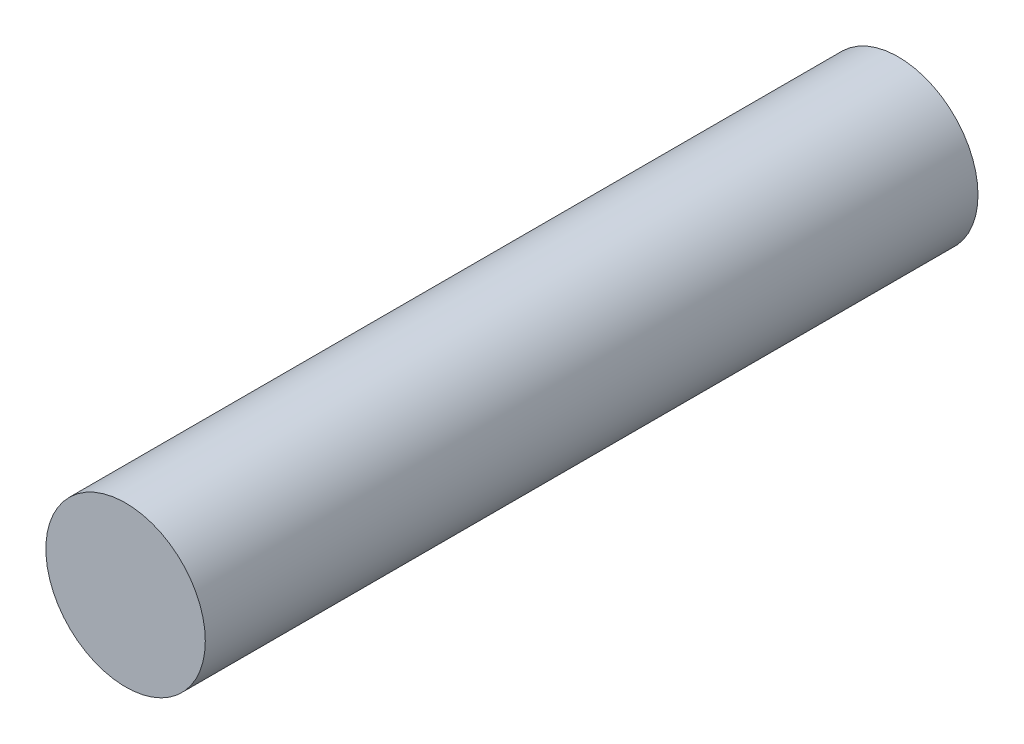
SolidWorks part; units mm, degrees
ref_plane "Front Plane" through (0, 0, 0) normal (0, 0, 1) x (1, 0, 0)
ref_plane "Top Plane" through (0, 0, 0) normal (0, 1, 0) x (1, 0, 0)
ref_plane "Right Plane" through (0, 0, 0) normal (1, 0, 0) x (0, 0, -1)
sketch "Sketch1" plane through (0, 0, 0) normal (0, 0, 1) x (1, 0, 0)
  circle A0 centre (0, 0) radius 1.651
  dimension "D1" = 3.302
extrude "Boss-Extrude1" add sketch "Sketch1" along normal blind 16 contours A0
